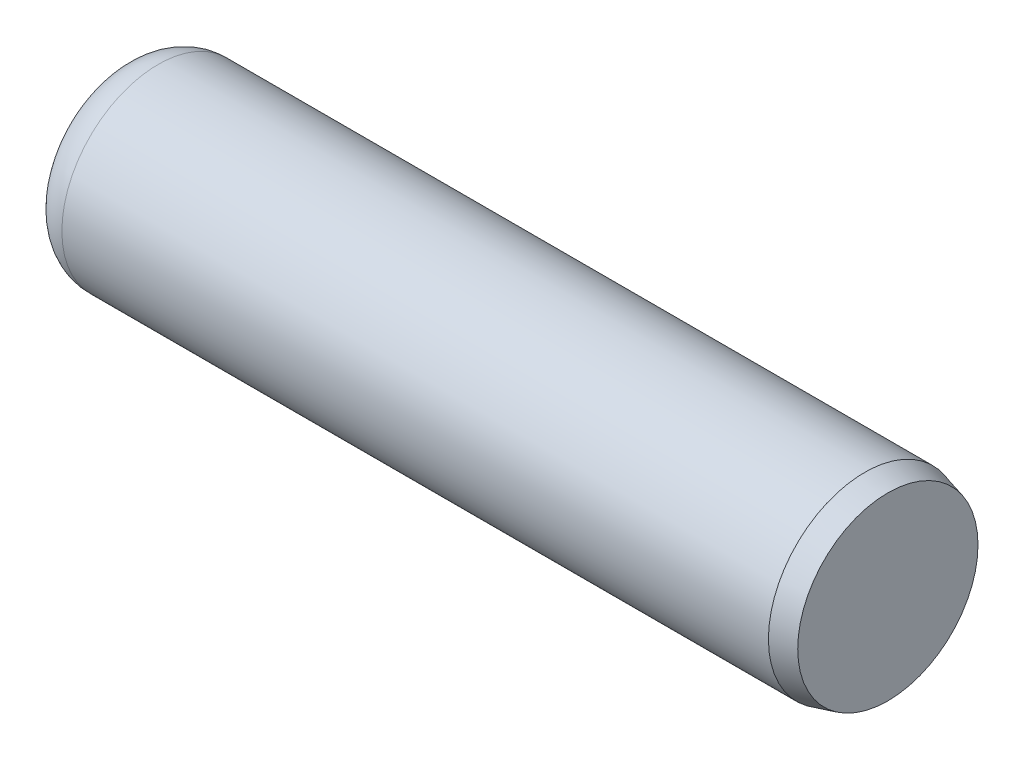
SolidWorks part; units mm, degrees
ref_plane "Plane1" through (0, 0, 0) normal (0, 0, 1) x (1, 0, 0)
ref_plane "Plane2" through (0, 0, 0) normal (0, 1, 0) x (1, 0, 0)
ref_plane "Plane3" through (0, 0, 0) normal (1, 0, 0) x (0, 0, -1)
sketch "Sketch1" plane through (0, 0, 0) normal (0, 0, 1) x (1, 0, 0)
  line L1 (-6.35, 0) -> (107.95, 0) construction
  line L2 (0, 0) -> (6.35, 0)
  line L3 (6.35, 0) -> (6.35, 0.7451)
  line L4 (6.35, 0.7451) -> (6.1589, 0.7963)
  line L5 (6.1589, 0.7963) -> (0.3185, 0.7963)
  line L6 (0, 0.4778) -> (0, 0)
  arc A0 (0.3185, 0.7963) -> (0, 0.4778) centre (0.3185, 0.4778) ccw
  dimension "D4" = 0.3185
  dimension "D2" = 0.1911
  dimension "D3" = 15
  dimension "Diameter" = 1.5926
  dimension "Length" = 6.35
revolve "Base-Revolve" add sketch "Sketch1" angle 360 about L1
